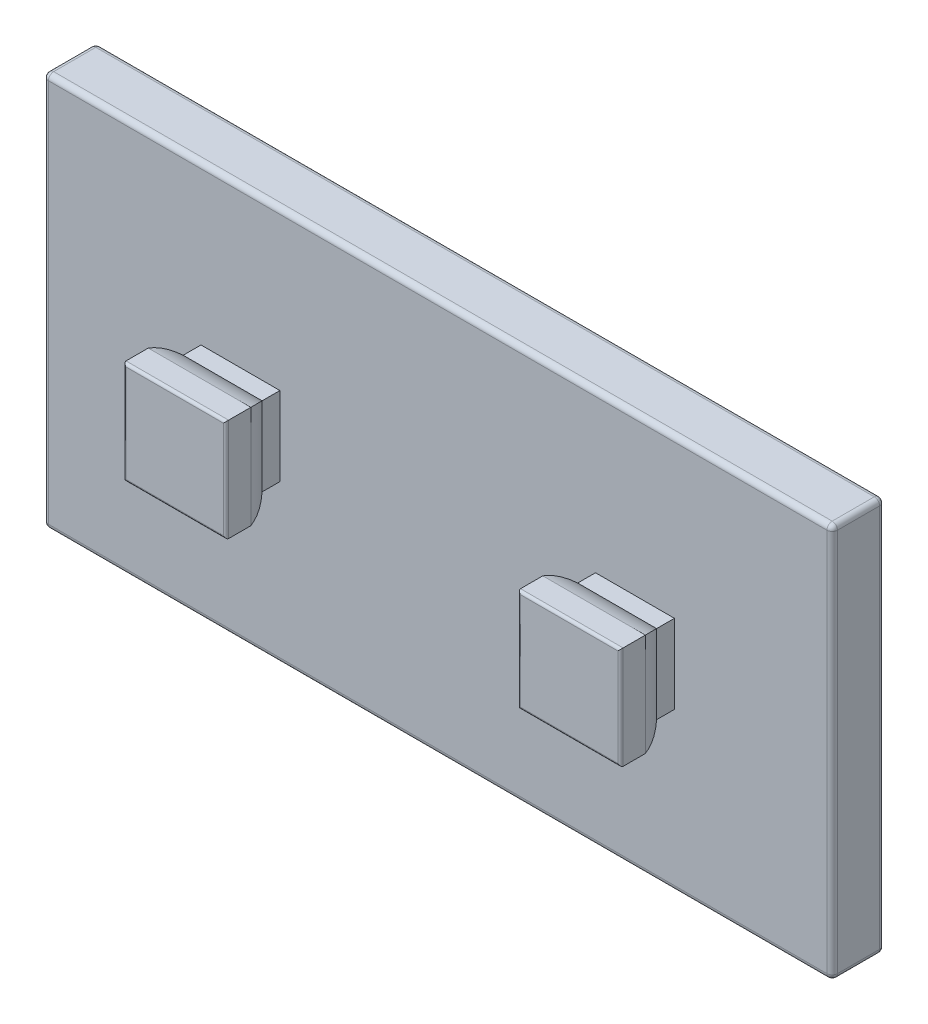
SolidWorks part; units mm, degrees
ref_plane "前视基准面" through (0, 0, 0) normal (0, 0, 1) x (1, 0, 0)
ref_plane "上视基准面" through (0, 0, 0) normal (0, 1, 0) x (1, 0, 0)
ref_plane "右视基准面" through (0, 0, 0) normal (1, 0, 0) x (0, 0, -1)
sketch "草图1" plane through (0, 0, 0) normal (0, 0, 1) x (1, 0, 0)
  line L1 (-7.5, -7.5) -> (22.5, -7.5)
  line L2 (-7.5, -7.5) -> (-7.5, 7.5)
  line L3 (-7.5, 7.5) -> (22.5, 7.5)
  line L4 (22.5, -7.5) -> (22.5, 7.5)
extrude "凸台-拉伸1" add sketch "草图1" against normal blind 2
sketch "草图2" plane through (0, 0, 0) normal (0, 0, 1) x (1, 0, 0)
  line L1 (-1.5, -1.5) -> (1.5, -1.5)
  line L2 (-1.5, -1.5) -> (-1.5, 1.5)
  line L3 (-1.5, 1.5) -> (1.5, 1.5)
  line L4 (1.5, -1.5) -> (1.5, 1.5)
extrude "凸台-拉伸2" add sketch "草图2" along normal blind 1
sketch "草图3" plane through (0, 0, 0) normal (0, 1, 0) x (1, 0, 0)
  line L0 (-1.95, -2.5) -> (1.95, -2.5)
  line L1 (-1.95, -2.5) -> (-1.95, -1.5556)
  line L2 (-1.5, -1) -> (-1.5, 0) construction
  line L3 (-1.5, -0.6771) -> (1.5, -0.6771)
  line L4 (1.95, -2.5) -> (1.95, -1.5556)
  arc A0 (1.95, -1.5556) -> (1.5, -0.6771) centre (0, -2) ccw
  arc A1 (-1.5, -0.6771) -> (-1.95, -1.5556) centre (0, -2) ccw
extrude "凸台-拉伸3" add sketch "草图3" along normal blind 2 and the other way blind 2
sketch "草图4" plane through (0, 0, 0) normal (1, 0, 0) x (0, 0, -1)
  line L0 (-2.5, 1.95) -> (-1.5556, 1.95)
  line L1 (-2.5, 1.95) -> (-2.5, 2)
  line L2 (-2.5, -2) -> (-2.5, 2) construction
  line L3 (-2.5, 2) -> (-0.6771, 2)
  line L4 (-0.6771, 2) -> (-0.6771, 1.5)
  line L5 (-2.5, -2) -> (-0.6771, -2)
  line L6 (-0.6771, -2) -> (-0.6771, -1.5)
  line L7 (-2.5, -1.95) -> (-1.5556, -1.95)
  line L8 (-2.5, -1.95) -> (-2.5, -2)
  arc A0 (-0.6771, 1.5) -> (-1.5556, 1.95) centre (-2, 0) ccw
  arc A2 (-1.5556, -1.95) -> (-0.6771, -1.5) centre (-2, 0) ccw
extrude "切除-拉伸1" cut sketch "草图4" against normal up to next and the other way up to next
fillet "圆角1" radius 0.1 4 edges at (0, -1.95, 2.5) (-1.95, 0, 2.5) (0, 1.95, 2.5) (1.95, 0, 2.5)
ref_plane "基准面1" through (7.5, 0, 0) normal (1, 0, 0) x (0, 0, -1)
mirror "镜向1" about plane through (7.5, 0, 0) normal (1, 0, 0) of "凸台-拉伸2", "凸台-拉伸3", "切除-拉伸1", "圆角1"
fillet "圆角3" radius 0.2 12 edges at (7.5, -7.5, -2) (7.5, -7.5, 0) (-7.5, -7.5, -1) (-7.5, 0, -2) (-7.5, 0, 0) (22.5, 0, -2) (22.5, -7.5, -1) (22.5, 0, 0) (-7.5, 7.5, -1) (7.5, 7.5, -2) (22.5, 7.5, -1) (7.5, 7.5, 0)
